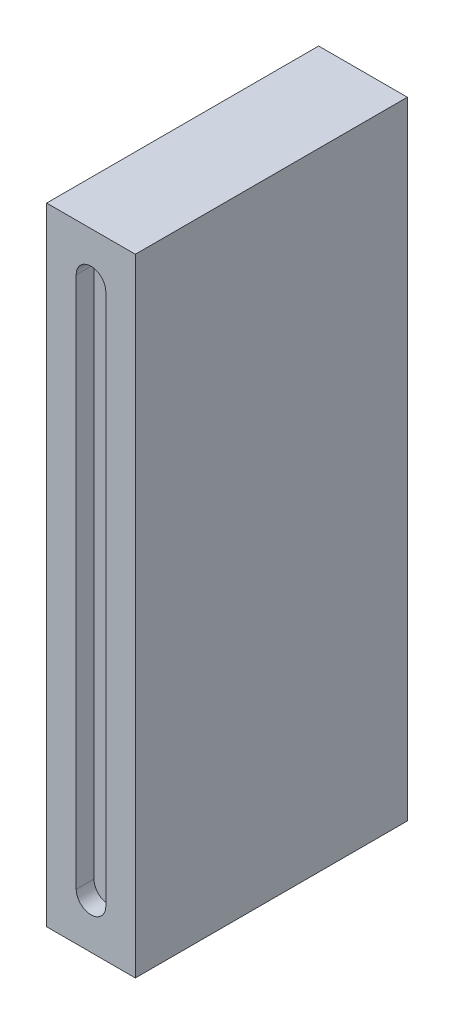
SolidWorks part; units mm, degrees
ref_plane "Front Plane" through (0, 0, 0) normal (0, 0, 1) x (1, 0, 0)
ref_plane "Top Plane" through (0, 0, 0) normal (0, 1, 0) x (1, 0, 0)
ref_plane "Right Plane" through (0, 0, 0) normal (1, 0, 0) x (0, 0, -1)
sketch "Sketch4" plane through (0, 0, 0) normal (0, 0, 1) x (1, 0, 0)
  line L1 (7.5, -50) -> (-7.5, -50)
  line L2 (7.5, -50) -> (7.5, 50)
  line L3 (7.5, 50) -> (-7.5, 50)
  line L4 (-7.5, -50) -> (-7.5, 50)
  line L5 (7.5, -50) -> (-7.5, 50) construction
  line L6 (7.5, 50) -> (-7.5, -50) construction
  point P0 (0, 0)
  dimension "D1" = 15
  dimension "D2" = 100
extrude "Boss-Extrude1" add sketch "Sketch4" along normal blind 5
sketch "Sketch5" plane through (7.5, 0, 0) normal (1, 0, 0) x (0, 0, -1)
  line L0 (0, 8.25) -> (0, -8.25) construction
  line L1 (0, -50) -> (36, -50)
  line L2 (0, -50) -> (0, 50)
  line L3 (0, 50) -> (36, 50)
  line L4 (36, -50) -> (36, 50)
  line L5 (-5, -50) -> (0, -50) construction
  line L6 (-5, 50) -> (0, 50) construction
  dimension "D1" = 36
extrude "Boss-Extrude2" add sketch "Sketch5" against normal blind 5
ref_plane "Plane1" through (0, 0, -18) normal (0, 0, 1) x (1, 0, 0)
mirror "Mirror1" about plane through (0, 0, -18) normal (0, 0, 1) of "Boss-Extrude1"
sketch "Sketch6" plane through (0, 0, 5) normal (0, 0, 1) x (1, 0, 0)
  line L0 (0, 45) -> (0, -45) construction
  line L1 (2.5, 45) -> (2.5, -45)
  line L2 (-2.5, 45) -> (-2.5, -45)
  arc A0 (2.5, 45) -> (-2.5, 45) centre (0, 45) ccw
  arc A1 (-2.5, -45) -> (2.5, -45) centre (0, -45) ccw
  point P3 (0, 0)
  point P8 (2.5, 0)
  dimension "D2" = 90
  dimension "D1" = 5
extrude "Cut-Extrude1" cut sketch "Sketch6" against normal blind 3
mirror "Mirror2" about plane through (0, 0, -18) normal (0, 0, 1) of "Cut-Extrude1"
sketch "Sketch7" plane through (0, -50, 0) normal (0, -1, 0) x (1, 0, 0)
  line L1 (-7.5, 5) -> (7.5, 5)
  line L2 (-7.5, 5) -> (-7.5, -41)
  line L3 (-7.5, -41) -> (7.5, -41)
  line L4 (7.5, 5) -> (7.5, -41)
extrude "Boss-Extrude3" add sketch "Sketch7" along normal blind 3
mirror "Mirror3" about plane through (0, 0, 0) normal (0, 1, 0) of "Boss-Extrude3"
